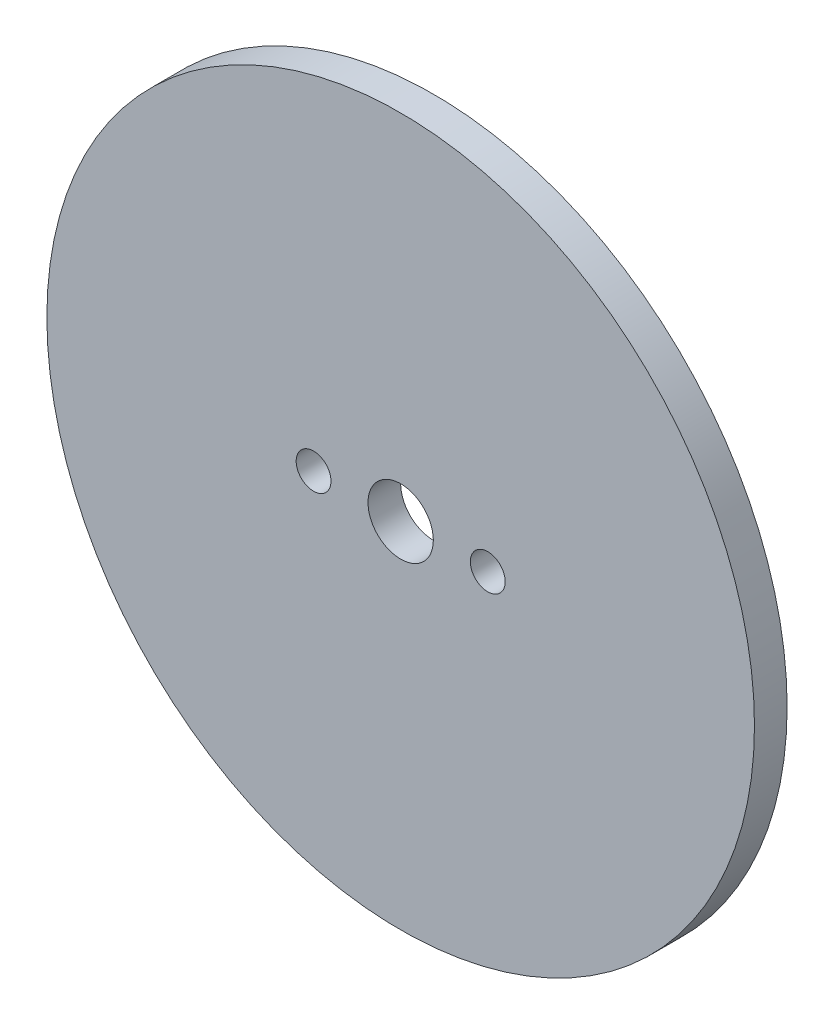
SolidWorks part; units mm, degrees
ref_plane "Plano frontal" through (0, 0, 0) normal (0, 0, 1) x (1, 0, 0)
ref_plane "Plano superior" through (0, 0, 0) normal (0, 1, 0) x (1, 0, 0)
ref_plane "Plano direito" through (0, 0, 0) normal (1, 0, 0) x (0, 0, -1)
sketch "Esboço1" plane through (0, 0, 0) normal (0, 0, 1) x (1, 0, 0)
  line L0 (-8, 0) -> (8, 0) construction
  circle A0 centre (0, 0) radius 32.5
  circle A1 centre (0, 0) radius 3
  circle A2 centre (-8, 0) radius 1.6
  circle A3 centre (8, 0) radius 1.6
  dimension "D1" = 3.2
  dimension "D2" = 6
  dimension "D4" = 65
  dimension "D3" = 16
extrude "Ressalto-extrusão1" add sketch "Esboço1" along normal mid plane 3
